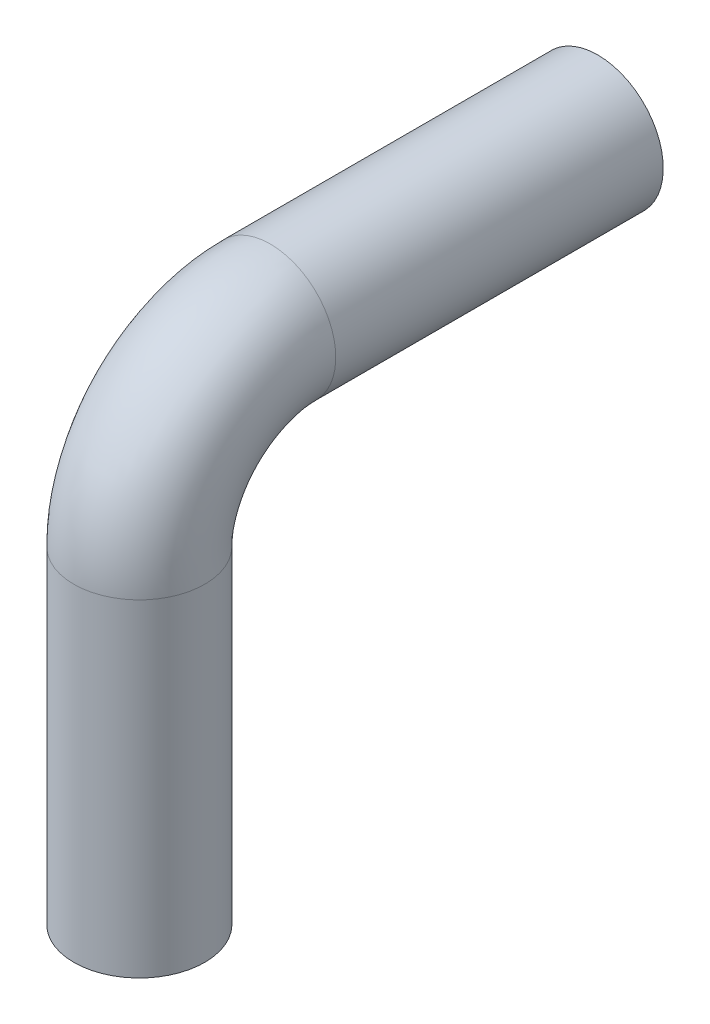
SolidWorks part; units mm, degrees
ref_plane "Front Plane" through (0, 0, 0) normal (0, 0, 1) x (1, 0, 0)
ref_plane "Top Plane" through (0, 0, 0) normal (0, 1, 0) x (1, 0, 0)
ref_plane "Right Plane" through (0, 0, 0) normal (1, 0, 0) x (0, 0, -1)
sketch "Sketch1" plane through (0, 0, 0) normal (0, 1, 0) x (1, 0, 0)
  circle A0 centre (0, 0) radius 12.7
  dimension "D1" = 25.4
sketch "Sketch2" plane through (0, 0, 0) normal (1, 0, 0) x (0, 0, -1)
  line L0 (0, 0) -> (0, 63.5)
  line L1 (25.4, 88.9) -> (88.9, 88.9)
  arc A0 (0, 63.5) -> (25.4, 88.9) centre (25.4, 63.5) cw
  point P6 (0, 88.9)
  dimension "D3" = 25.4
  dimension "D1" = 88.9
  dimension "D2" = 88.9
sweep "Sweep1" add profiles "Sketch1" path "Sketch2"
sketch "Sketch3" plane through (0, 0, 0) normal (1, 0, 0) x (0, 0, -1)
  line L0 (25.4, 101.6) -> (88.9, 101.6) construction
